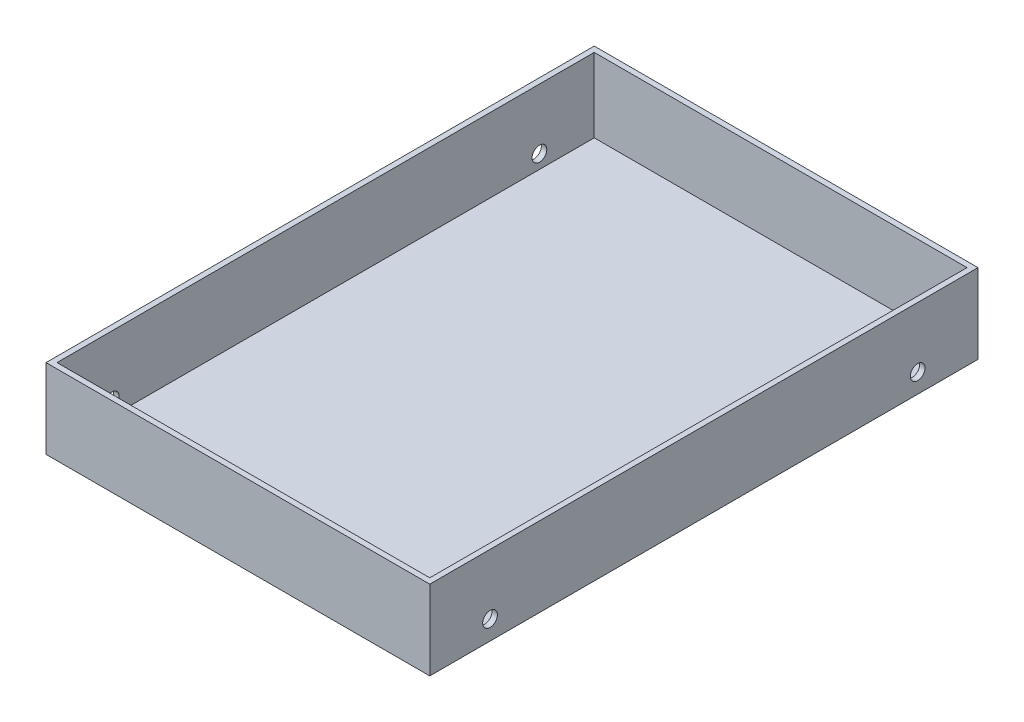
SolidWorks part; units mm, degrees
material "Acrylic (Medium-high impact)"
ref_plane "Front Plane" through (0, 0, 0) normal (0, 0, 1) x (1, 0, 0)
ref_plane "Top Plane" through (0, 0, 0) normal (0, 1, 0) x (1, 0, 0)
ref_plane "Right Plane" through (0, 0, 0) normal (1, 0, 0) x (0, 0, -1)
sketch "Sketch1" plane through (0, 0, 0) normal (0, 1, 0) x (1, 0, 0)
  line L1 (-175, -250) -> (175, -250)
  line L2 (-175, -250) -> (-175, 250)
  line L3 (-175, 250) -> (175, 250)
  line L4 (175, -250) -> (175, 250)
  line L5 (-175, -250) -> (175, 250) construction
  line L6 (-175, 250) -> (175, -250) construction
  point P1 (0, 0)
  dimension "D1" = 500
  dimension "D2" = 350
extrude "Boss-Extrude1" add sketch "Sketch1" along normal blind 72.5
shell "Shell1" thickness 5
sketch "Sketch2" plane through (175, 0, 0) normal (1, 0, 0) x (0, 0, -1)
  line L1 (-250, 72.5) -> (250, 72.5) construction
  line L2 (-250, 0) -> (250, 0) construction
  line L3 (-250, 72.5) -> (-250, 0) construction
  line L4 (0, -36.33) -> (0, 129.6327) construction
  circle A0 centre (-195, 17.5) radius 6.7231
  circle A1 centre (195, 17.5) radius 6.7231
  dimension "D1" = 55
  dimension "D2" = 17.5
  dimension "D3" = 55
extrude "Cut-Extrude1" cut sketch "Sketch2" against normal through all both and the other way through all
